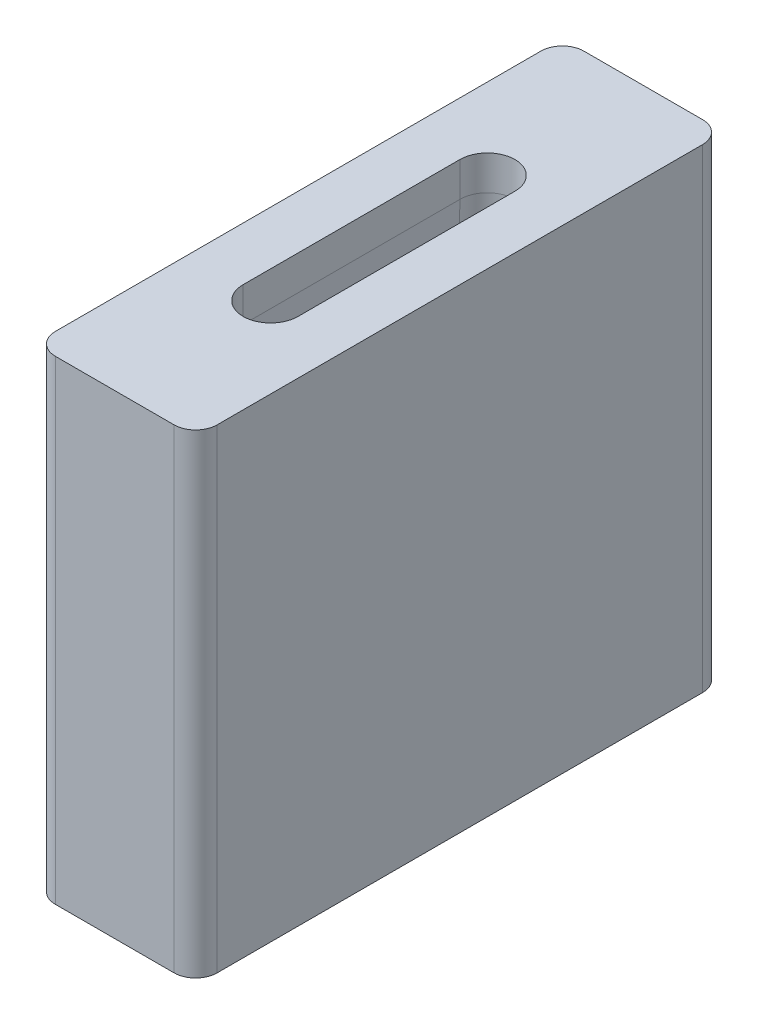
SolidWorks part; units mm, degrees
material "K110"
ref_plane "Front Plane" through (0, 0, 0) normal (0, 0, 1) x (1, 0, 0)
ref_plane "Top Plane" through (0, 0, 0) normal (0, 1, 0) x (1, 0, 0)
ref_plane "Right Plane" through (0, 0, 0) normal (1, 0, 0) x (0, 0, -1)
sketch "Sketch1" plane through (0, 0, 0) normal (0, 1, 0) x (1, 0, 0)
  line L3 (0, -3.5) -> (0, 3.5) construction
  line L4 (-2.62, -3.5) -> (-2.62, 3.5) construction
  line L5 (2.62, -3.5) -> (2.62, 3.5) construction
  line L6 (-5.5, -24.5) -> (5.5, -24.5)
  line L7 (-7.5, -22.5) -> (-7.5, 22.5)
  line L8 (-5.5, 24.5) -> (5.5, 24.5)
  line L9 (7.5, -22.5) -> (7.5, 22.5)
  line L10 (-7.5, -24.5) -> (7.5, 24.5) construction
  line L11 (-7.5, 24.5) -> (7.5, -24.5) construction
  arc A2 (-2.62, -3.5) -> (2.62, -3.5) centre (0, -3.5) ccw construction
  arc A3 (2.62, 3.5) -> (-2.62, 3.5) centre (0, 3.5) ccw construction
  arc A4 (-5.5, -24.5) -> (-7.5, -22.5) centre (-5.5, -22.5) cw
  arc A5 (5.5, -24.5) -> (7.5, -22.5) centre (5.5, -22.5) ccw
  arc A6 (5.5, 24.5) -> (7.5, 22.5) centre (5.5, 22.5) cw
  arc A7 (-7.5, 22.5) -> (-5.5, 24.5) centre (-5.5, 22.5) cw
  point P0 (0, 0)
  point P10 (0, 0)
  dimension "D1" = 7
  dimension "D3" = 2.62
  dimension "D5" = 2
  dimension "D2" = 49
  dimension "D4" = 15
extrude "Boss-Extrude1" add sketch "Sketch1" against normal blind 44
sketch "Sketch5" plane through (0, 0, 0) normal (0, 1, 0) x (1, 0, 0)
  line L0 (0, -10.05) -> (0, 10.05) construction
  line L1 (-2.55, -10.05) -> (-2.55, 10.05)
  line L2 (2.55, -10.05) -> (2.55, 10.05)
  arc A0 (-2.55, -10.05) -> (2.55, -10.05) centre (0, -10.05) ccw
  arc A1 (2.55, 10.05) -> (-2.55, 10.05) centre (0, 10.05) ccw
  point P4 (0, 0)
  dimension "D1" = 20.1
  dimension "D2" = 5.1
extrude "Cut-Extrude2" cut sketch "Sketch5" against normal up to next
sketch "Sketch7" plane through (0, 0, 0) normal (0, 0, 1) x (1, 0, 0)
  line L0 (2.55, -3.2) -> (3.2622, -44)
  line L1 (2.55, -44) -> (2.55, 0) construction
  line L2 (-5.5, -44) -> (5.5, -44) construction
  line L3 (3.2622, -44) -> (2.55, -44)
  line L4 (2.55, -44) -> (2.55, -3.2)
  line L5 (7.5, 0) -> (5.5, 0) construction
  dimension "D1" = 3.2
  dimension "D2" = 1
sketch "Sketch8" plane through (0, 0, 0) normal (0, 1, 0) x (1, 0, 0)
  line L0 (-2.55, 10.05) -> (-2.55, -10.05) construction
  line L1 (2.55, -10.05) -> (2.55, 10.05) construction
  line L2 (-2.55, 10.05) -> (-2.55, -10.05)
  line L3 (2.55, -10.05) -> (2.55, 10.05)
  arc A0 (2.55, 10.05) -> (-2.55, 10.05) centre (0, 10.05) ccw construction
  arc A1 (-2.55, -10.05) -> (2.55, -10.05) centre (0, -10.05) ccw construction
  arc A2 (2.55, 10.05) -> (-2.55, 10.05) centre (0, 10.05) ccw
  arc A3 (-2.55, -10.05) -> (2.55, -10.05) centre (0, -10.05) ccw
sweep "Cut-Sweep1" cut profiles "Sketch7" path "Sketch8"
hole_wizard "M6 Tapped Hole1" positions "Sketch11" profile "Sketch10" tap size "M6" standard "ISO"
sketch "Sketch11" plane through (0, -44, 0) normal (0, -1, 0) x (-1, 0, 0)
  line L0 (-5.5, 24.5) -> (5.5, 24.5) construction
  line L5 (5.5, -24.5) -> (-5.5, -24.5) construction
  line L6 (0, 24.5) -> (0, -24.5) construction
  point P0 (0, 20.5)
  point P2 (0, -20.5)
  dimension "D1" = 4
  dimension "D4" = 4
sketch "Sketch10" plane through (0, -44, -20.5) normal (1, 0, 0) x (0, 0, -1)
  line L0 (0, 0) -> (0, 18.5022)
  line L1 (0, 18.5022) -> (2.5, 17)
  line L2 (2.5, 17) -> (2.5, 0.525)
  line L3 (2.5, 0.525) -> (3.025, 0)
  line L5 (3.025, 0) -> (0, 0)
  line L6 (-2.5, 0.525) -> (-3.025, 0) construction
  line L10 (0, 18.5022) -> (-2.5, 17) construction
  line L11 (0, -6.35) -> (0, 107.95) construction
  dimension "Tap Drill Dia." = 5
  dimension "Tap Drill Depth" = 17
  dimension "Near C'Sink Dia." = 6.05
  dimension "Near C'Sink Angle" = 90
  dimension "Drill Angle" = 118
cosmetic thread "Hole Thread1"
cosmetic thread "Hole Thread2"
